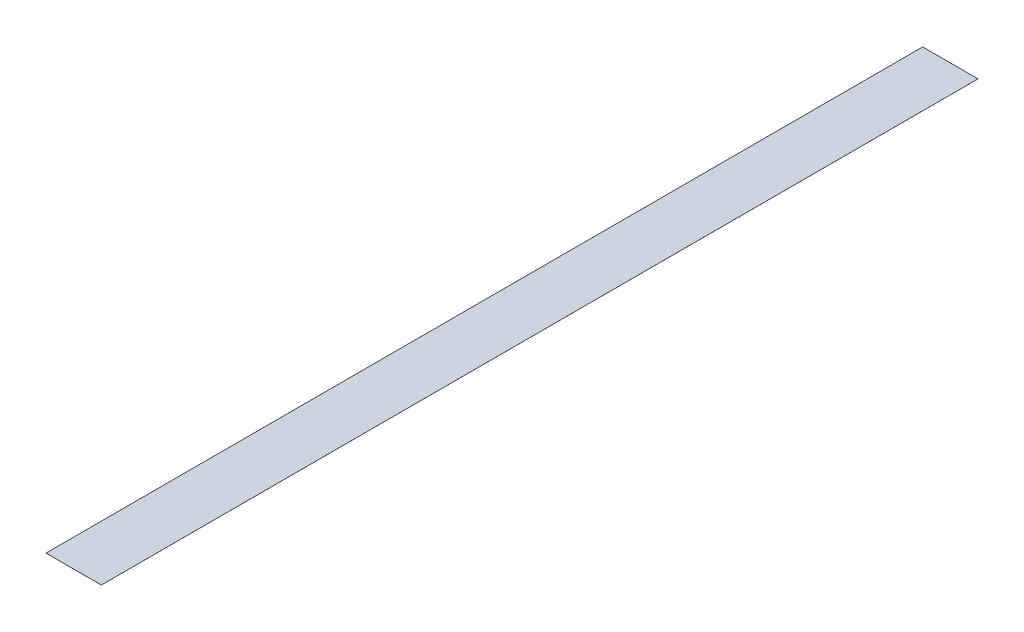
SolidWorks part; units mm, degrees
ref_plane "Plano frontal" through (0, 0, 0) normal (0, 0, 1) x (1, 0, 0)
ref_plane "Plano superior" through (0, 0, 0) normal (0, 1, 0) x (1, 0, 0)
ref_plane "Plano direito" through (0, 0, 0) normal (1, 0, 0) x (0, 0, -1)
sketch "Esboço1" plane through (0, 0, 0) normal (0, 1, 0) x (1, 0, 0)
  line L0 (-1093, 595.536) -> (-1073, 595.536)
  line L1 (0, 0) -> (18.9344, 0)
  line L2 (0, 0) -> (0, 766.8662)
  line L3 (0, 766.8662) -> (18.9344, 766.8662)
  line L4 (18.9344, 0) -> (18.9344, 766.8662)
  line L5 (-381.6968, 766.8662) -> (-362.7624, 766.8662)
  line L6 (-381.6968, 766.8662) -> (-381.6968, 345.536)
  line L7 (-381.6968, 345.536) -> (-362.7624, 345.536)
  line L8 (-362.7624, 766.8662) -> (-362.7624, 345.536)
  line L9 (-858.9344, 645.536) -> (-840, 645.536)
  line L10 (-858.9344, 645.536) -> (-858.9344, 345.536)
  line L11 (-858.9344, 345.536) -> (-840, 345.536)
  line L12 (-840, 645.536) -> (-840, 345.536)
  line L13 (-853.5858, 925.2213) -> (-1253.5858, 925.2213)
  line L14 (-853.5858, 925.2213) -> (-853.5858, 945.2213)
  line L15 (-853.5858, 945.2213) -> (-1253.5858, 945.2213)
  line L16 (-1253.5858, 925.2213) -> (-1253.5858, 945.2213)
  line L17 (-1093, 595.536) -> (-1093, 195.536)
  line L18 (-1093, 195.536) -> (-1073, 195.536)
  line L19 (-1073, 595.536) -> (-1073, 195.536)
  line L21 (-858.9344, 427.7897) -> (-1250.0103, 427.7897)
  line L23 (-858.9344, 407.7897) -> (-1250.0103, 407.7897)
  line L24 (-1250.0103, 427.7897) -> (-1250.0103, 407.7897)
  line L33 (-1439.6613, 239.7512) -> (-1560.0448, 239.7512)
  line L34 (-1439.6613, 239.7512) -> (-1439.6613, 219.7512)
  line L35 (-1439.6613, 219.7512) -> (-1560.0448, 219.7512)
  line L36 (-1560.0448, 239.7512) -> (-1560.0448, 219.7512)
  line L37 (-1627.2015, 576.144) -> (-1607.2015, 576.144)
  line L38 (-1627.2015, 576.144) -> (-1627.2015, 317.0654)
  line L39 (-1627.2015, 317.0654) -> (-1607.2015, 317.0654)
  line L40 (-1607.2015, 576.144) -> (-1607.2015, 317.0654)
  line L41 (-1627.2015, 769.6927) -> (-1607.2015, 769.6927)
  line L42 (-1627.2015, 769.6927) -> (-1627.2015, 1019.6927)
  line L43 (-1627.2015, 1019.6927) -> (-1607.2015, 1019.6927)
  line L44 (-1607.2015, 769.6927) -> (-1607.2015, 1019.6927)
  line L61 (558.7805, 1049.2726) -> (577.7149, 1049.2726)
  line L62 (558.7805, 1049.2726) -> (558.7805, 749.2726)
  line L63 (558.7805, 749.2726) -> (577.7149, 749.2726)
  line L64 (577.7149, 1049.2726) -> (577.7149, 749.2726)
  arc A6 (-381.6968, 766.8662) -> (18.9344, 766.8662) centre (-181.3812, 766.8662) cw
  arc A7 (-362.7624, 766.8662) -> (0, 766.8662) centre (-181.3812, 766.8662) cw
  arc A8 (-362.7624, 345.536) -> (-858.9344, 345.536) centre (-610.8484, 345.536) cw
  arc A9 (-381.6968, 345.536) -> (-840, 345.536) centre (-610.8484, 345.536) cw
  arc A10 (-840, 645.536) -> (-803.6955, 702.0415) centre (-777.8744, 645.536) cw
  arc A11 (-803.6955, 702.0415) -> (-853.5858, 945.2213) centre (-856.6336, 817.8884) ccw
  arc A12 (-858.9344, 645.536) -> (-814.4955, 717.9247) centre (-777.7563, 645.536) cw
  arc A13 (-814.4955, 717.9247) -> (-853.5858, 925.2213) centre (-864.2122, 815.8835) ccw
  arc A14 (-1093, 595.536) -> (-1188.5366, 677.9223) centre (-1176.2913, 595.536) ccw
  arc A15 (-1188.5366, 677.9223) -> (-1354.3411, 742.8189) centre (-1214.8489, 854.9525) cw
  arc A16 (-1354.3411, 742.8189) -> (-1253.5858, 945.2213) centre (-1257.3278, 820.805) cw
  arc A17 (-1073, 595.536) -> (-1188.5366, 698.0004) centre (-1176.2038, 595.536) ccw
  arc A18 (-1188.5366, 698.0004) -> (-1341.8208, 766.8662) centre (-1207.9995, 859.705) cw
  arc A19 (-1341.8208, 766.8662) -> (-1253.5858, 925.2213) centre (-1258.876, 824.4093) cw
  arc A22 (-1368.7558, 309.7722) -> (-1439.6613, 219.7512) centre (-1474.849, 320.402) cw
  arc A23 (-1388.5562, 309.7722) -> (-1439.6613, 239.7512) centre (-1477.6183, 321.1143) cw
  arc A24 (-1388.5562, 309.7722) -> (-1250.0103, 427.7897) centre (-1254.4723, 292.6965) cw
  arc A25 (-1607.2015, 317.0654) -> (-1560.0448, 239.7512) centre (-1520.2441, 317.0654) ccw
  arc A26 (-1627.2015, 317.0654) -> (-1560.0448, 219.7512) centre (-1523.1159, 317.0654) ccw
  arc A27 (-1368.7558, 309.7722) -> (-1250.0103, 407.7897) centre (-1259.9289, 298.8686) cw
extrude "Ressalto-extrusão9" add sketch "Esboço1" along normal blind 0.01 contours L64 L63 L62 L61
